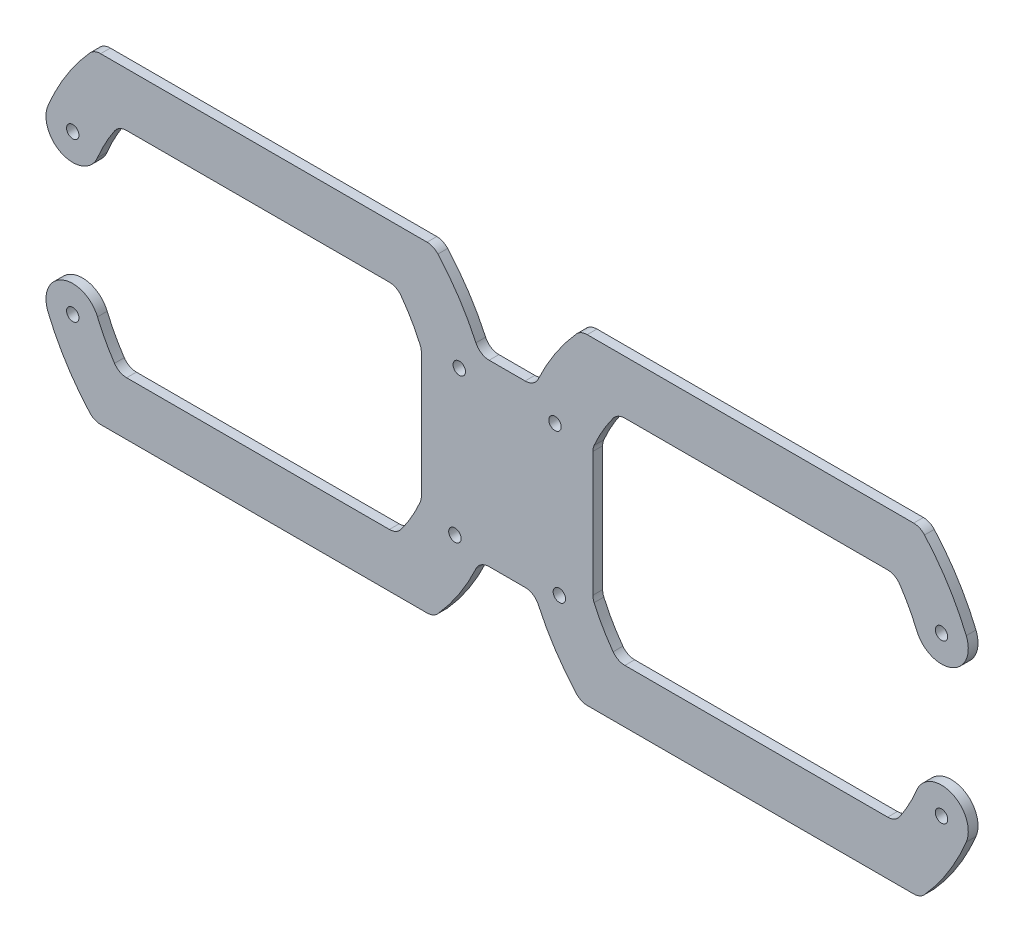
SolidWorks part; units mm, degrees
ref_plane "前视基准面" through (0, 0, 0) normal (0, 0, 1) x (1, 0, 0)
ref_plane "上视基准面" through (0, 0, 0) normal (0, 1, 0) x (1, 0, 0)
ref_plane "右视基准面" through (0, 0, 0) normal (1, 0, 0) x (0, 0, -1)
sketch "草图1" plane through (0, 0, 0) normal (0, 0, 1) x (1, 0, 0)
  line L3 (-50, 48) -> (50, 48)
  line L4 (-50, -48) -> (50, -48)
  arc A4 (-50, 48) -> (-50, -48) centre (-50, 0) ccw
  arc A5 (50, 48) -> (50, -48) centre (50, 0) cw
extrude "凸台-拉伸1" add sketch "草图1" along normal blind 2
hole_wizard "M2.5 螺旋的螺纹孔钻头1" positions "3D草图1" profile "草图3" hole size "M2.5x0.45" standard "BSI" end condition through all
sketch3d "3D草图1"
  point P56 (-89.2649, 16.264, 2)
  point P63 (-66.264, 39.2649, 2)
  point P77 (-33.736, 39.2649, 2)
  point P157 (-33.736, -39.2649, 2)
  point P158 (-66.264, -39.2649, 2)
  point P159 (-89.2649, -16.264, 2)
  point P196 (-9.8309, 13.8815, 2)
  point P198 (-10.7351, -16.264, 2)
  point P210 (10.7351, -16.264, 2)
  point P211 (9.8309, 13.8815, 2)
  point P212 (89.2649, -16.264, 2)
  point P213 (66.264, -39.2649, 2)
  point P214 (33.736, -39.2649, 2)
  point P215 (33.736, 39.2649, 2)
  point P216 (66.264, 39.2649, 2)
  point P217 (89.2649, 16.264, 2)
sketch "草图3" plane through (-89.2649, 16.264, 2) normal (1, 0, 0) x (0, -1, 0)
  line L0 (0, 0) -> (0, 2)
  line L1 (0, 2) -> (1.275, 2)
  line L2 (1.275, 2) -> (1.275, 0)
  line L5 (1.275, 0) -> (0, 0)
  line L11 (0, -6.35) -> (0, 107.95) construction
  dimension "通孔孔直径" = 2.55
  dimension "通孔孔深度" = 2
sketch "草图5" plane through (0, 0, 0) normal (0, 0, 1) x (1, 0, 0)
  line L2 (1.1, 0) -> (-1.1, 0) construction
  line L4 (-17.6246, -13.4103) -> (-17.6246, 13.4103)
  line L6 (-5.6538, -18.3688) -> (5.6538, -18.3688)
  line L7 (-50, -22) -> (-22.7236, -22)
  line L8 (-50, -22) -> (-79.7489, -22)
  line L10 (-50, -33) -> (-84.8569, -33)
  line L11 (-50, -33) -> (-15.1431, -33)
  line L12 (0, -1.1) -> (0, 1.1) construction
  line L13 (50, -33) -> (15.1431, -33)
  line L14 (50, -33) -> (84.8569, -33)
  line L15 (17.6246, 13.4103) -> (17.6246, -13.4103)
  line L16 (50, -22) -> (79.7489, -22)
  line L17 (50, -22) -> (22.7236, -22)
  line L20 (50, 22) -> (79.7489, 22)
  line L21 (50, 33) -> (15.1431, 33)
  line L22 (50, 33) -> (84.8569, 33)
  line L23 (50, 22) -> (22.7236, 22)
  line L24 (-5.6538, 18.3688) -> (5.6538, 18.3688)
  line L25 (-50, 33) -> (-15.1431, 33)
  line L26 (-50, 33) -> (-84.8569, 33)
  line L27 (-50, 22) -> (-79.7489, 22)
  line L28 (-50, 22) -> (-22.7236, 22)
  arc A9 (-50, 48) -> (-50, -48) centre (-50, 0) ccw construction
  arc A29 (-84.1835, -14.1593) -> (-94.3462, -18.3688) centre (-89.2649, -16.264) ccw
  arc A63 (-79.7489, -22) -> (-84.1835, -14.1593) centre (-50, 0) cw
  arc A64 (-22.7236, -22) -> (-17.6246, -13.4103) centre (-50, 0) ccw
  arc A65 (-15.1431, -33) -> (-5.6538, -18.3688) centre (-50, 0) ccw
  arc A66 (-84.8569, -33) -> (-94.3462, -18.3688) centre (-50, 0) cw
  arc A67 (84.8569, -33) -> (94.3462, -18.3688) centre (50, 0) ccw
  arc A68 (15.1431, -33) -> (5.6538, -18.3688) centre (50, 0) cw
  arc A69 (22.7236, -22) -> (17.6246, -13.4103) centre (50, 0) cw
  arc A70 (79.7489, -22) -> (84.1835, -14.1593) centre (50, 0) ccw
  arc A71 (84.1835, -14.1593) -> (94.3462, -18.3688) centre (89.2649, -16.264) cw
  arc A85 (84.8569, 33) -> (94.3462, 18.3688) centre (50, 0) cw
  arc A86 (84.1835, 14.1593) -> (94.3462, 18.3688) centre (89.2649, 16.264) ccw
  arc A87 (79.7489, 22) -> (84.1835, 14.1593) centre (50, 0) cw
  arc A88 (22.7236, 22) -> (17.6246, 13.4103) centre (50, 0) ccw
  arc A89 (15.1431, 33) -> (5.6538, 18.3688) centre (50, 0) ccw
  arc A90 (-15.1431, 33) -> (-5.6538, 18.3688) centre (-50, 0) cw
  arc A91 (-84.8569, 33) -> (-94.3462, 18.3688) centre (-50, 0) ccw
  arc A92 (-84.1835, 14.1593) -> (-94.3462, 18.3688) centre (-89.2649, 16.264) cw
  arc A93 (-79.7489, 22) -> (-84.1835, 14.1593) centre (-50, 0) ccw
  arc A94 (-22.7236, 22) -> (-17.6246, 13.4103) centre (-50, 0) cw
  point P21 (17.6246, 0)
  point P54 (-17.6246, 0)
  point P55 (-17.6246, 0)
  point P74 (17.6246, 0)
extrude "切除-拉伸1" cut sketch "草图5" along normal blind 10 flip side to cut
fillet "圆角1" radius 3 24 edges at (22.7236, -22, 1) (79.7489, -22, 1) (84.8569, -33, 1) (15.1431, -33, 1) (-5.6538, -18.3688, 1) (5.6538, -18.3688, 1) (-15.1431, -33, 1) (-79.7489, -22, 1) (-22.7236, -22, 1) (-84.8569, -33, 1) (5.6538, 18.3688, 1) (84.8569, 33, 1) (79.7489, 22, 1) (17.6246, 13.4103, 1) (17.6246, -13.4103, 1) (-17.6246, -13.4103, 1) (-17.6246, 13.4103, 1) (22.7236, 22, 1) (-15.1431, 33, 1) (15.1431, 33, 1) (-5.6538, 18.3688, 1) (-22.7236, 22, 1) (-79.7489, 22, 1) (-84.8569, 33, 1)
